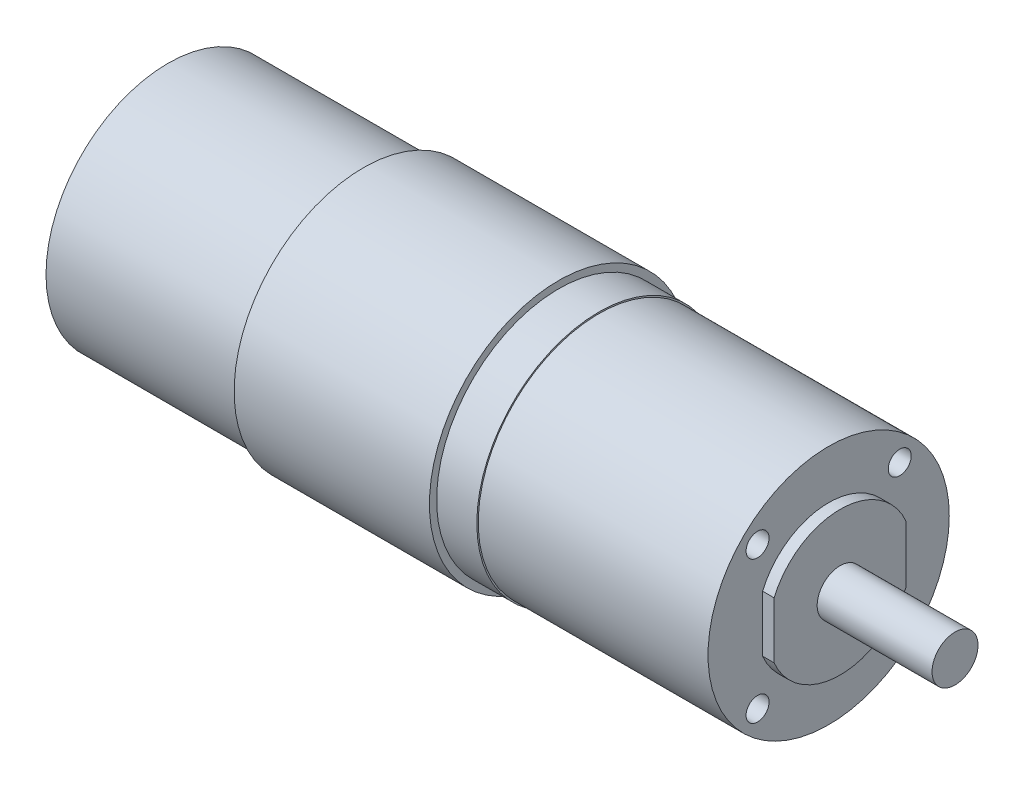
SolidWorks part; units mm, degrees
ref_plane "Front Plane" through (0, 0, 0) normal (0, 0, 1) x (1, 0, 0)
ref_plane "Top Plane" through (0, 0, 0) normal (0, 1, 0) x (1, 0, 0)
ref_plane "Right Plane" through (0, 0, 0) normal (1, 0, 0) x (0, 0, -1)
sketch "Sketch1" plane through (0, 0, 0) normal (1, 0, 0) x (0, 0, -1)
  circle A0 centre (0, 0) radius 21
  dimension "D1" = 42
extrude "Boss-Extrude1" add sketch "Sketch1" along normal blind 40
sketch "Sketch2" plane through (40, 0, 0) normal (1, 0, 0) x (0, 0, -1)
  line L0 (0, 12.5) -> (0, -12.5) construction
  line L1 (-11.5, 4.899) -> (-11.5, -4.899)
  line L2 (11.5, 4.899) -> (11.5, -4.899)
  arc A0 (-11.5, -4.899) -> (11.5, -4.899) centre (0, 0) ccw
  arc A1 (11.5, 4.899) -> (-11.5, 4.899) centre (0, 0) ccw
  dimension "D1" = 25
  dimension "D2" = 11.5
extrude "Boss-Extrude2" add sketch "Sketch2" along normal blind 2
sketch "Sketch3" plane through (42, 0, 0) normal (1, 0, 0) x (0, 0, -1)
  circle A0 centre (0, 0) radius 4
  dimension "D1" = 8
extrude "Boss-Extrude3" add sketch "Sketch3" along normal blind 20
sketch "Sketch4" plane through (40, 0, 0) normal (1, 0, 0) x (0, 0, -1)
  line L0 (0, 21) -> (0, -21) construction
  line L1 (0, 0) -> (-14.8492, 14.8492) construction
  circle A0 centre (0, 0) radius 21 construction
  circle A1 centre (-12.3744, 12.3744) radius 2
  circle A2 centre (12.3744, 12.3744) radius 2
  circle A3 centre (12.3744, -12.3744) radius 2
  circle A4 centre (-12.3744, -12.3744) radius 2
  point P19 (0, 0)
  dimension "D3" = 4
  dimension "D1" = 45
  dimension "D2" = 17.5
  dimension "D4" = 4
extrude "Cut-Extrude1" cut sketch "Sketch4" against normal blind 10
sketch "Sketch5" plane through (0, 0, 0) normal (-1, 0, 0) x (0, 0, 1)
  circle A0 centre (0, 0) radius 21.25
  dimension "D1" = 42.5
extrude "Boss-Extrude4" add sketch "Sketch5" along normal blind 75
ref_plane "Plane1" through (-7, 0, 0) normal (1, 0, 0) x (0, 0, -1)
sketch "Sketch6" plane through (-7, 0, 0) normal (1, 0, 0) x (0, 0, -1)
  circle A0 centre (0, 0) radius 22.5
  circle A1 centre (0, 0) radius 21.25 construction
  circle A2 centre (0, 0) radius 21.25
  dimension "D1" = 45
extrude "Boss-Extrude5" add sketch "Sketch6" against normal blind 34
